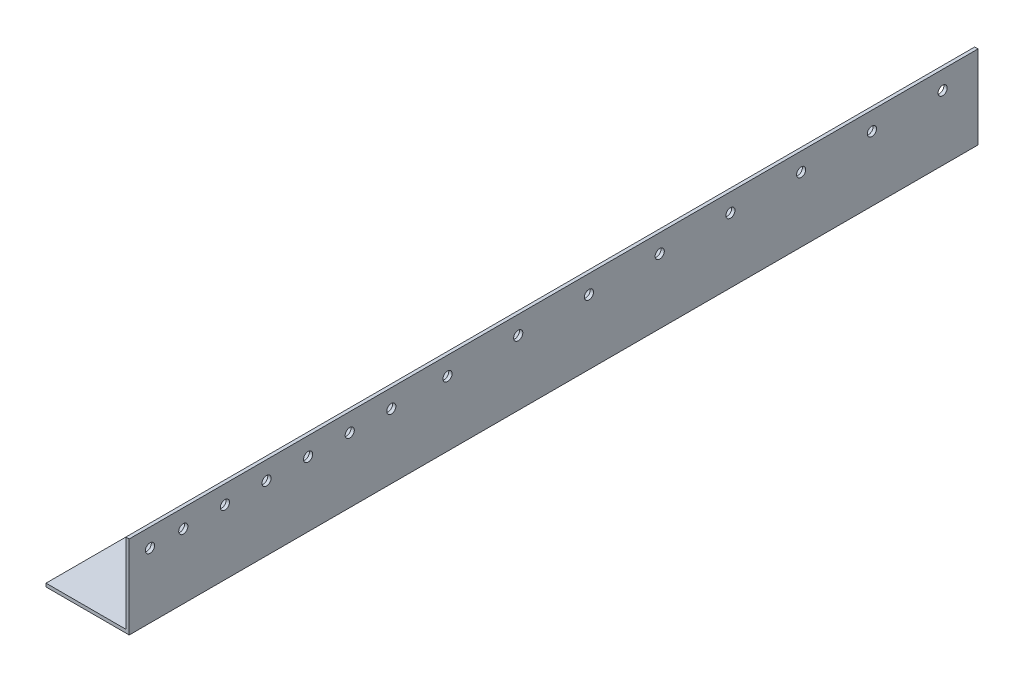
SolidWorks part; units mm, degrees
ref_plane "Front Plane" through (0, 0, 0) normal (0, 0, 1) x (1, 0, 0)
ref_plane "Top Plane" through (0, 0, 0) normal (0, 1, 0) x (1, 0, 0)
ref_plane "Right Plane" through (0, 0, 0) normal (1, 0, 0) x (0, 0, -1)
sketch "Sketch1" plane through (0, 0, 0) normal (0, 0, 1) x (1, 0, 0)
  line L0 (0, 0) -> (-50, 0)
  line L1 (-50, 0) -> (-50, 2)
  line L2 (-50, 2) -> (-2, 2)
  line L3 (-2, 2) -> (-2, 50)
  line L4 (-2, 50) -> (0, 50)
  line L5 (0, 50) -> (0, 0)
extrude "Boss-Extrude1" add sketch "Sketch1" along normal blind 510
sketch "Sketch2" plane through (0, 0, 0) normal (1, 0, 0) x (0, 0, -1)
  circle A0 centre (-21.25, 39) radius 2.75
  circle A1 centre (-63.75, 39) radius 2.75
  circle A2 centre (-106.25, 39) radius 2.75
  circle A3 centre (-148.75, 39) radius 2.75
  circle A4 centre (-191.25, 39) radius 2.75
  circle A5 centre (-233.75, 39) radius 2.75
  circle A6 centre (-276.25, 39) radius 2.75
  circle A7 centre (-318.75, 39) radius 2.75
  circle A8 centre (-352.5, 39) radius 2.75
  circle A9 centre (-377.5, 39) radius 2.75
  circle A10 centre (-402.5, 39) radius 2.75
  circle A11 centre (-427.5, 39) radius 2.75
  circle A12 centre (-452.5, 39) radius 2.75
  circle A13 centre (-477.5, 39) radius 2.75
  circle A14 centre (-497.5, 39) radius 2.75
extrude "Cut-Extrude1" cut sketch "Sketch2" against normal mid plane 10
